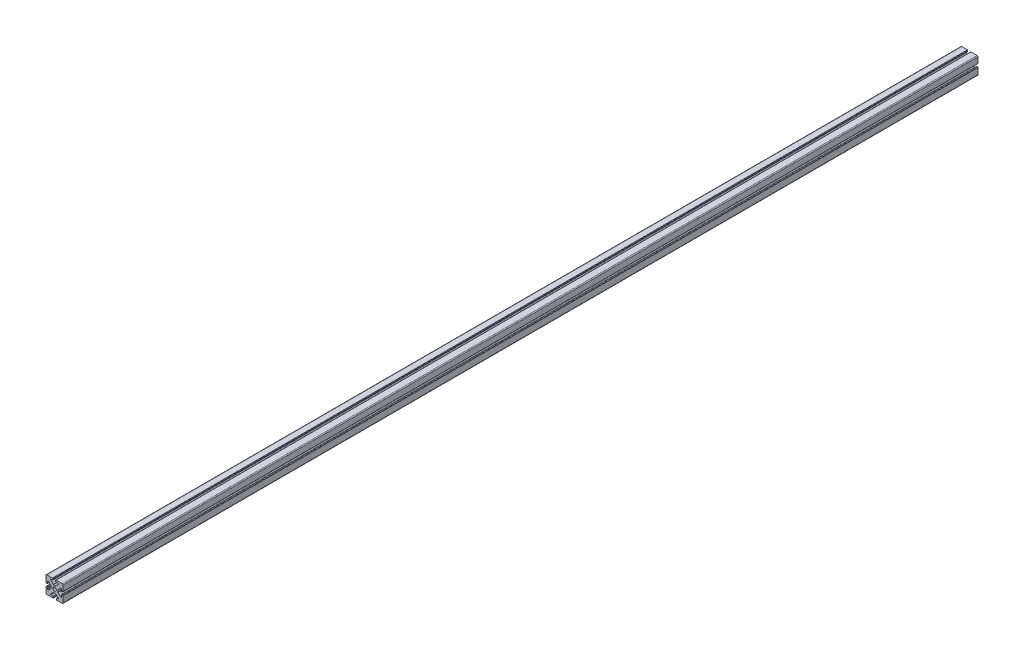
SolidWorks part; units mm, degrees
ref_plane "Front" through (0, 0, 0) normal (0, 0, 1) x (1, 0, 0)
ref_plane "Top" through (0, 0, 0) normal (0, 1, 0) x (1, 0, 0)
ref_plane "Right" through (0, 0, 0) normal (1, 0, 0) x (0, 0, -1)
sketch "草图1" plane through (0, 0, 0) normal (0, 0, 1) x (1, 0, 0)
  line L1 (-20, 20) -> (20, 20)
  line L2 (-20, 20) -> (-20, -20)
  line L3 (-20, -20) -> (20, -20)
  line L4 (20, 20) -> (20, -20)
  line L5 (-20, 20) -> (20, -20) construction
  line L6 (-20, -20) -> (20, 20) construction
  point P0 (0, 0)
  dimension "D1" = 40
extrude "凸台-拉伸1" add sketch "草图1" along normal blind 2140
sketch "草图2" plane through (0, 0, 2140) normal (0, 0, 1) x (1, 0, 0)
  circle A0 centre (0, 0) radius 4.05
  dimension "D1" = 8.1
extrude "切除-拉伸1" cut sketch "草图2" against normal blind 10000
sketch "草图4" plane through (0, 0, 2140) normal (0, 0, 1) x (1, 0, 0)
  line L0 (20, -20) -> (20, 20) construction
  line L1 (20, 0) -> (20, 4)
  line L2 (20, 0) -> (20, -2.652)
  line L3 (7.8769, 2.6) -> (7.8769, -2.6)
  line L4 (20, 4) -> (16, 4)
  line L5 (20, -2.652) -> (16, -2.652)
  line L6 (16, 10.5) -> (16, 4)
  line L7 (16, 10.5) -> (7.8769, 2.6)
  line L8 (16, -10.5) -> (7.8769, -2.6)
  line L9 (16, -2.652) -> (16, -10.5)
  point P11 (7.8769, 0)
  point P12 (16, 0)
extrude "切除-拉伸2" cut sketch "草图4" against normal blind 10000
fillet "圆角1" radius 1 8 edges at (16, 10.5, 1070) (16, -10.5, 1070) (7.8769, 2.6, 1070) (20, -2.652, 1070) (16, -2.652, 1070) (20, 4, 1070) (16, 4, 1070) (7.8769, -2.6, 1070)
pattern_circular "阵列(圆周)2" count 4 over 360 about axis through (0, 0, 0) along (0, 0, 1) of "切除-拉伸2"
fillet "圆角2" radius 1 8 edges at (10.5, 16, 1070) (-10.5, 16, 1070) (-4, 20, 1070) (2.652, 16, 1070) (2.652, 20, 1070) (-2.6, 7.8769, 1070) (-4, 16, 1070) (2.6, 7.8769, 1070)
fillet "圆角3" radius 1 8 edges at (-7.8769, -2.6, 1070) (-7.8769, 2.6, 1070) (-20, 2.652, 1070) (-16, 10.5, 1070) (-20, -4, 1070) (-16, -4, 1070) (-16, -10.5, 1070) (-16, 2.652, 1070)
fillet "圆角4" radius 1 8 edges at (4, -20, 1070) (4, -16, 1070) (10.5, -16, 1070) (-2.652, -20, 1070) (2.6, -7.8769, 1070) (-2.6, -7.8769, 1070) (-2.652, -16, 1070) (-10.5, -16, 1070)
fillet "圆角5" radius 2 4 edges at (-20, -20, 1070) (20, -20, 1070) (-20, 20, 1070) (20, 20, 1070)
